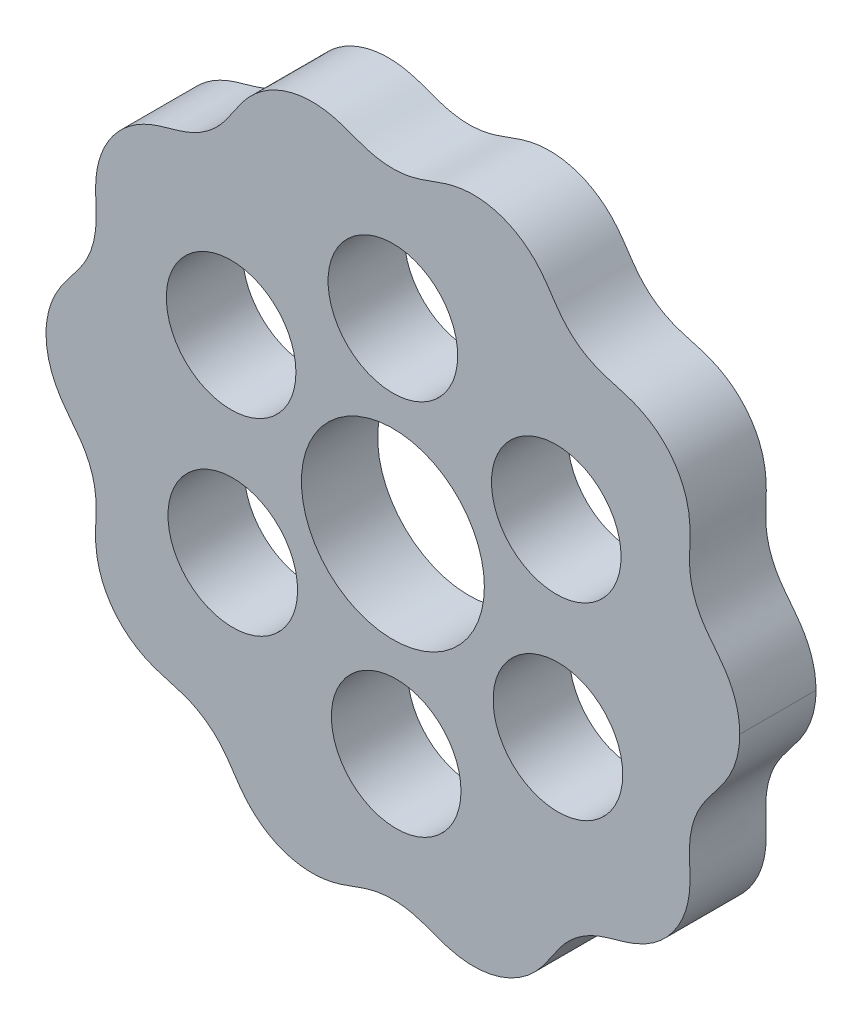
SolidWorks part; units mm, degrees
ref_plane "Front Plane" through (0, 0, 0) normal (0, 0, 1) x (1, 0, 0)
ref_plane "Top Plane" through (0, 0, 0) normal (0, 1, 0) x (1, 0, 0)
ref_plane "Right Plane" through (0, 0, 0) normal (1, 0, 0) x (0, 0, -1)
sketch "Sketch1" plane through (0, 0, 0) normal (0, 0, 1) x (1, 0, 0)
  line L3 (-51.157, 0) -> (64.2707, 0) construction
  spline S0 degree 3 poles (-45.5, 0) (-45.4994, 0.5465) (-45.4186, 1.6369) (-45.0624, 3.2355) (-44.4776, 4.7704) (-43.8026, 5.9938) (-43.1176, 6.9949) (-42.4996, 7.8097) (-41.83, 8.6425) (-41.1102, 9.6029) (-40.4625, 10.5757) (-39.7576, 11.9256) (-39.2158, 13.5555) (-38.9726, 15.0822) (-38.9163, 16.281) (-38.9275, 17.1995) (-38.9638, 18.1754) (-39.0033, 19.1221) (-39.004, 20.0816) (-38.9556, 20.9623) (-38.8541, 21.8012) (-38.6458, 22.8868) (-38.2467, 24.1919) (-37.5479, 25.6709) (-36.6423, 27.0336) (-35.5495, 28.2509) (-34.292, 29.2974) (-33.1241, 30.0137) (-32.11, 30.4971) (-31.298, 30.8206) (-30.4007, 31.1182) (-29.3423, 31.423) (-28.152, 31.7477) (-26.7594, 32.2403) (-25.4426, 32.8531) (-24.0236, 33.7972) (-22.851, 34.9014) (-22.0451, 35.8732) (-21.2912, 36.9201) (-20.6802, 37.8567) (-20.0885, 38.7188) (-19.5319, 39.4544) (-18.9696, 40.11) (-18.3833, 40.7074) (-17.5598, 41.4365) (-16.4474, 42.2254) (-14.9906, 42.9692) (-13.4409, 43.4947) (-11.8323, 43.7906) (-10.1966, 43.8508) (-8.8306, 43.7046) (-7.7185, 43.4672) (-6.856, 43.2247) (-5.9156, 42.9064) (-4.9711, 42.5506) (-3.9426, 42.1854) (-2.9365, 41.8746) (-1.5918, 41.5788) (0.0844, 41.4531) (1.7371, 41.6123) (3.0311, 41.9165) (4.0066, 42.2263) (4.9998, 42.5836) (5.9354, 42.9356) (6.8644, 43.2483) (7.726, 43.4881) (8.835, 43.7213) (10.2019, 43.8632) (11.8367, 43.7973) (13.4445, 43.4959) (14.9923, 42.9651) (16.4466, 42.2163) (17.5564, 41.4236) (18.3781, 40.6913) (18.9632, 40.0912) (19.5251, 39.4322) (20.0831, 38.6909) (20.6803, 37.8189) (21.3054, 36.8627) (22.0917, 35.7869) (22.9377, 34.7931) (24.1547, 33.6921) (25.5849, 32.7854) (26.8686, 32.2129) (28.22, 31.7482) (29.3831, 31.4333) (30.4264, 31.1319) (31.3177, 30.8343) (32.1266, 30.5093) (33.1374, 30.0235) (34.3025, 29.3036) (35.5563, 28.2528) (36.645, 27.0318) (37.5459, 25.6659) (38.2397, 24.185) (38.7135, 22.6153) (38.923, 21.2441) (38.9845, 20.0661) (38.9819, 19.0993) (38.9413, 18.1388) (38.9069, 17.1388) (38.9012, 16.1912) (38.9736, 14.9525) (39.2521, 13.3934) (39.8297, 11.778) (40.5349, 10.4831) (41.1739, 9.5436) (41.8741, 8.62) (42.535, 7.7985) (43.1447, 6.992) (43.8231, 5.9955) (44.4943, 4.7693) (45.0732, 3.2367) (45.3365, 2.0299) (45.4377, 1.2313) (45.4748, 0.8083) (45.4916, 0.5025) (45.4981, 0.2317) (45.4999, 0.0765) (45.5, 0.0278) (45.5, 0) knots 0.499999 0.499999 0.499999 0.499999 0.506686 0.513342 0.519997 0.526653 0.529981 0.533309 0.536636 0.5383 0.539964 0.541628 0.543292 0.544956 0.54662 0.548284 0.549947 0.553275 0.556603 0.559931 0.563259 0.566586 0.573242 0.579897 0.586553 0.593209 0.599864 0.60652 0.609847 0.613175 0.616503 0.619831 0.623159 0.624822 0.626486 0.62815 0.629814 0.631478 0.633142 0.63647 0.639797 0.643125 0.646453 0.649781 0.653109 0.659764 0.66642 0.673075 0.679731 0.686386 0.693042 0.69637 0.699697 0.703025 0.706353 0.708017 0.709681 0.711345 0.713009 0.714672 0.716336 0.718 0.719664 0.722992 0.72632 0.729647 0.732975 0.739631 0.746286 0.752942 0.759597 0.766253 0.772909 0.776236 0.779564 0.782892 0.78622 0.789547 0.792875 0.794539 0.796203 0.797867 0.799531 0.801195 0.802858 0.806186 0.809514 0.812842 0.81617 0.819497 0.826153 0.832808 0.839464 0.84612 0.852775 0.859431 0.866086 0.869414 0.872742 0.87607 0.877733 0.879397 0.881061 0.882725 0.884389 0.886053 0.887717 0.889381 0.892708 0.896036 0.899364 0.90602 0.912675 0.919331 0.920995 0.922658 0.924322 0.925154 0.92557 0.925984 0.925984 0.925984 0.925984
  spline S3 degree 3 poles (-45.5, 0) (-45.4994, -0.5465) (-45.4186, -1.6369) (-45.0624, -3.2355) (-44.4776, -4.7704) (-43.8026, -5.9938) (-43.1176, -6.9949) (-42.4996, -7.8097) (-41.83, -8.6425) (-41.1102, -9.6029) (-40.4625, -10.5757) (-39.7576, -11.9256) (-39.2158, -13.5555) (-38.9726, -15.0822) (-38.9163, -16.281) (-38.9275, -17.1995) (-38.9638, -18.1754) (-39.0033, -19.1221) (-39.004, -20.0816) (-38.9556, -20.9623) (-38.8541, -21.8012) (-38.6458, -22.8868) (-38.2467, -24.1919) (-37.5479, -25.6709) (-36.6423, -27.0336) (-35.5495, -28.2509) (-34.292, -29.2974) (-33.1241, -30.0137) (-32.11, -30.4971) (-31.298, -30.8206) (-30.4007, -31.1182) (-29.3423, -31.423) (-28.152, -31.7477) (-26.7594, -32.2403) (-25.4426, -32.8531) (-24.0236, -33.7972) (-22.851, -34.9014) (-22.0451, -35.8732) (-21.2912, -36.9201) (-20.6802, -37.8567) (-20.0885, -38.7188) (-19.5319, -39.4544) (-18.9696, -40.11) (-18.3833, -40.7074) (-17.5598, -41.4365) (-16.4474, -42.2254) (-14.9906, -42.9692) (-13.4409, -43.4947) (-11.8323, -43.7906) (-10.1966, -43.8508) (-8.8306, -43.7046) (-7.7185, -43.4672) (-6.856, -43.2247) (-5.9156, -42.9064) (-4.9711, -42.5506) (-3.9426, -42.1854) (-2.9365, -41.8746) (-1.5918, -41.5788) (0.0844, -41.4531) (1.7371, -41.6123) (3.0311, -41.9165) (4.0066, -42.2263) (4.9998, -42.5836) (5.9354, -42.9356) (6.8644, -43.2483) (7.726, -43.4881) (8.835, -43.7213) (10.2019, -43.8632) (11.8367, -43.7973) (13.4445, -43.4959) (14.9923, -42.9651) (16.4466, -42.2163) (17.5564, -41.4236) (18.3781, -40.6913) (18.9632, -40.0912) (19.5251, -39.4322) (20.0831, -38.6909) (20.6803, -37.8189) (21.3054, -36.8627) (22.0917, -35.7869) (22.9377, -34.7931) (24.1547, -33.6921) (25.5849, -32.7854) (26.8686, -32.2129) (28.22, -31.7482) (29.3831, -31.4333) (30.4264, -31.1319) (31.3177, -30.8343) (32.1266, -30.5093) (33.1374, -30.0235) (34.3025, -29.3036) (35.5563, -28.2528) (36.645, -27.0318) (37.5459, -25.6659) (38.2397, -24.185) (38.7135, -22.6153) (38.923, -21.2441) (38.9845, -20.0661) (38.9819, -19.0993) (38.9413, -18.1388) (38.9069, -17.1388) (38.9012, -16.1912) (38.9736, -14.9525) (39.2521, -13.3934) (39.8297, -11.778) (40.5349, -10.4831) (41.1739, -9.5436) (41.8741, -8.62) (42.535, -7.7985) (43.1447, -6.992) (43.8231, -5.9955) (44.4943, -4.7693) (45.0732, -3.2367) (45.3365, -2.0299) (45.4377, -1.2313) (45.4748, -0.8083) (45.4916, -0.5025) (45.4981, -0.2317) (45.4999, -0.0765) (45.5, -0.0278) (45.5, 0) knots 0.499999 0.499999 0.499999 0.499999 0.506686 0.513342 0.519997 0.526653 0.529981 0.533309 0.536636 0.5383 0.539964 0.541628 0.543292 0.544956 0.54662 0.548284 0.549947 0.553275 0.556603 0.559931 0.563259 0.566586 0.573242 0.579897 0.586553 0.593209 0.599864 0.60652 0.609847 0.613175 0.616503 0.619831 0.623159 0.624822 0.626486 0.62815 0.629814 0.631478 0.633142 0.63647 0.639797 0.643125 0.646453 0.649781 0.653109 0.659764 0.66642 0.673075 0.679731 0.686386 0.693042 0.69637 0.699697 0.703025 0.706353 0.708017 0.709681 0.711345 0.713009 0.714672 0.716336 0.718 0.719664 0.722992 0.72632 0.729647 0.732975 0.739631 0.746286 0.752942 0.759597 0.766253 0.772909 0.776236 0.779564 0.782892 0.78622 0.789547 0.792875 0.794539 0.796203 0.797867 0.799531 0.801195 0.802858 0.806186 0.809514 0.812842 0.81617 0.819497 0.826153 0.832808 0.839464 0.84612 0.852775 0.859431 0.866086 0.869414 0.872742 0.87607 0.877733 0.879397 0.881061 0.882725 0.884389 0.886053 0.887717 0.889381 0.892708 0.896036 0.899364 0.90602 0.912675 0.919331 0.920995 0.922658 0.924322 0.925154 0.92557 0.925984 0.925984 0.925984 0.925984
extrude "Boss-Extrude1" add sketch "Sketch1" along normal blind 10
sketch "Sketch2" plane through (0, 0, 10) normal (0, 0, 1) x (1, 0, 0)
  circle A0 centre (0, 0) radius 12
  circle A1 centre (0, 0) radius 24.5 construction
  circle A2 centre (0, 24.5) radius 8.5
  circle A3 centre (21.4341, 12.375) radius 8.5
  circle A4 centre (21.6506, -12.25) radius 8.5
  circle A5 centre (0.433, -24.75) radius 8.5
  circle A6 centre (-21.0011, -12.625) radius 8.5
  circle A7 centre (-21.2176, 12) radius 8.5
  point P18 (0.2165, -0.125)
  dimension "D1" = 24
  dimension "D2" = 49
  dimension "D3" = 17
  dimension "D4" = 6
extrude "Cut-Extrude2" cut sketch "Sketch2" against normal blind 10
